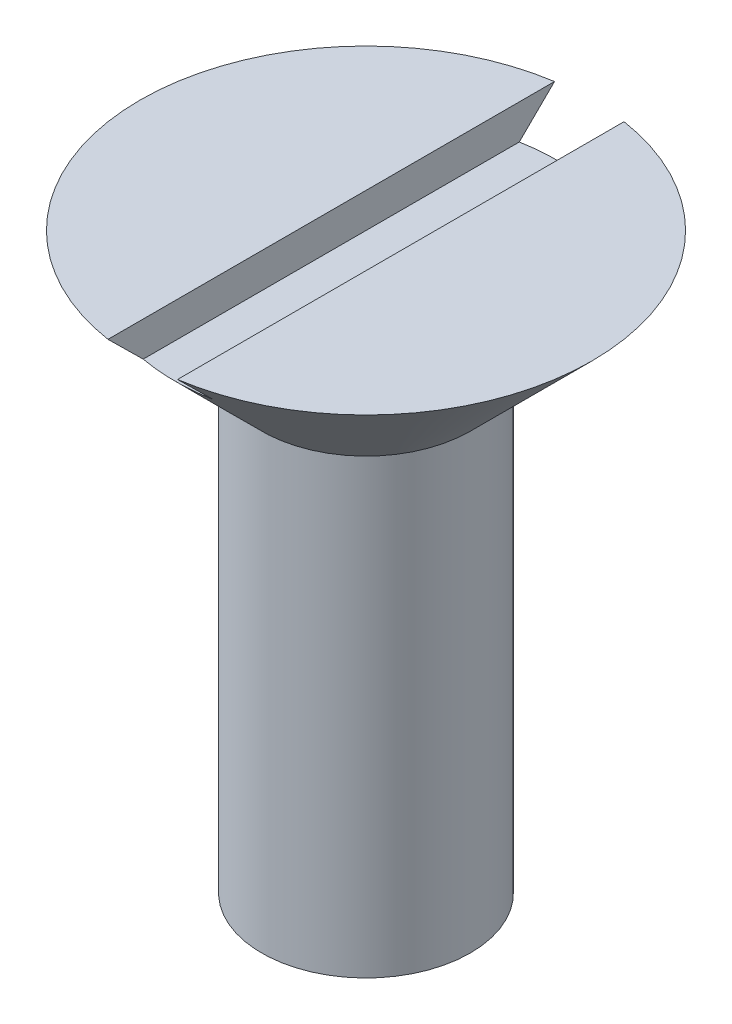
SolidWorks part; units mm, degrees
ref_plane "Front Plane" through (0, 0, 0) normal (0, 0, 1) x (1, 0, 0)
ref_plane "Top Plane" through (0, 0, 0) normal (0, 1, 0) x (1, 0, 0)
ref_plane "Right Plane" through (0, 0, 0) normal (1, 0, 0) x (0, 0, -1)
sketch "Sketch2" plane through (0, 0, 0) normal (0, 0, 1) x (1, 0, 0)
  line L0 (0, -1.2327) -> (0, -19.4648) construction
  line L1 (0, -1.2327) -> (6.5, -1.2327)
  line L2 (6.5, -1.2327) -> (3, -4.7327)
  line L3 (3, -4.7327) -> (3, -17.7327)
  line L4 (3, -17.7327) -> (0, -19.4648)
  line L5 (0, -1.2327) -> (0, -19.4648)
  dimension "D1" = 13
  dimension "D2" = 6.5
  dimension "D3" = 45
  dimension "D4" = 3
  dimension "D5" = 60
revolve "Revolve1" add sketch "Sketch2" angle 360 about L0
sketch "Sketch3" plane through (0, 0, 0) normal (0, 0, 1) x (1, 0, 0)
  line L0 (6.5, -1.2327) -> (-6.5, -1.2327) construction
  line L1 (-1, -0.2327) -> (1, -0.2327)
  line L2 (-1, -0.2327) -> (-1, -2.2327)
  line L3 (-1, -2.2327) -> (1, -2.2327)
  line L4 (1, -0.2327) -> (1, -2.2327)
  line L5 (-1, -0.2327) -> (1, -2.2327) construction
  line L6 (-1, -2.2327) -> (1, -0.2327) construction
  point P0 (0, -1.2327)
  point P7 (0, -2.2327)
  dimension "D1" = 2
  dimension "D2" = 1
extrude "Cut-Extrude1" cut sketch "Sketch3" against normal mid plane 30
